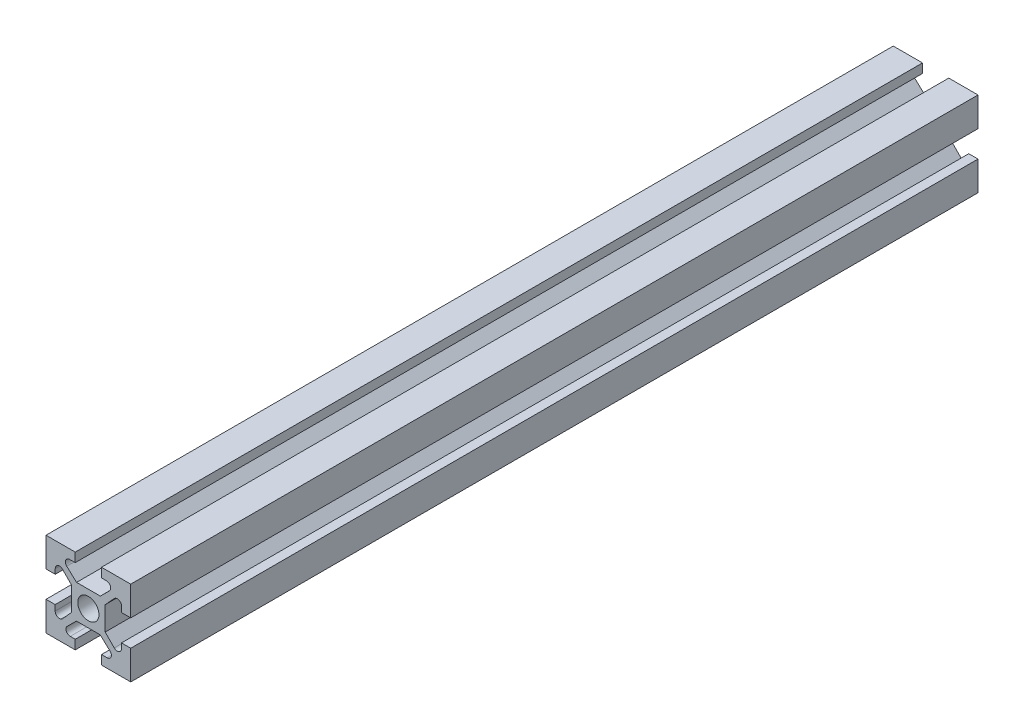
SolidWorks part; units mm, degrees
ref_plane "Front Plane" through (0, 0, 0) normal (0, 0, 1) x (1, 0, 0)
ref_plane "Top Plane" through (0, 0, 0) normal (0, 1, 0) x (1, 0, 0)
ref_plane "Right Plane" through (0, 0, 0) normal (1, 0, 0) x (0, 0, -1)
sketch "Sketch2" plane through (0, 0, 0) normal (0, 0, 1) x (1, 0, 0)
  line L0 (-295.6365, 99.3001) -> (355.6968, 99.3001) construction
  line L1 (53, 177) -> (305, 177) construction
  line L2 (0, 9.9554) -> (0, -10.0446) construction
  line L7 (-10, -10) -> (-3.1, -10)
  line L8 (-10, -10) -> (-10, -3.1)
  line L9 (-10, 10) -> (-3.1, 10)
  line L10 (10, -10) -> (10, -3.1)
  line L11 (-10, -10) -> (10, 10) construction
  line L12 (-10, 10) -> (10, -10) construction
  line L13 (-10, 0) -> (10, 0) construction
  line L14 (-10, 3.1) -> (-7.8186, 3.1)
  line L15 (-7.8186, 3.1) -> (-7.8186, 4.2854)
  line L16 (-6.1072, 4.9882) -> (-3.9647, 2.8197)
  line L17 (-3.9647, 2.8197) -> (-3.9647, 0)
  line L18 (-3.1, 10) -> (-3.1, 7.839)
  line L19 (-3.1, 7.839) -> (-4.4279, 7.839)
  line L20 (-5.1052, 6.1033) -> (-2.7827, 3.9647)
  line L21 (-2.7827, 3.9647) -> (0, 3.9647)
  line L22 (3.1, 10) -> (3.1, 7.8186)
  line L23 (3.1, 7.8186) -> (4.2854, 7.8186)
  line L24 (4.9882, 6.1072) -> (2.8197, 3.9647)
  line L25 (2.8197, 3.9647) -> (0, 3.9647)
  line L26 (6.1033, 5.1052) -> (3.9647, 2.7827)
  line L27 (3.9647, 2.7827) -> (3.9647, 0)
  line L28 (7.839, 3.1) -> (7.839, 4.4279)
  line L29 (10, 3.1) -> (7.839, 3.1)
  line L30 (10, -3.1) -> (7.8186, -3.1)
  line L31 (7.8186, -3.1) -> (7.8186, -4.2854)
  line L32 (6.1072, -4.9882) -> (3.9647, -2.8197)
  line L33 (3.9647, -2.8197) -> (3.9647, 0)
  line L34 (5.1052, -6.1033) -> (2.7827, -3.9647)
  line L35 (2.7827, -3.9647) -> (0, -3.9647)
  line L36 (3.1, -7.839) -> (4.4279, -7.839)
  line L37 (3.1, -10) -> (3.1, -7.839)
  line L38 (-3.1, -10) -> (-3.1, -7.8186)
  line L39 (-3.1, -7.8186) -> (-4.2854, -7.8186)
  line L40 (-4.9882, -6.1072) -> (-2.8197, -3.9647)
  line L41 (-2.8197, -3.9647) -> (0, -3.9647)
  line L42 (-6.1033, -5.1052) -> (-3.9647, -2.7827)
  line L43 (-3.9647, -2.7827) -> (-3.9647, 0)
  line L44 (-7.839, -3.1) -> (-7.839, -4.4279)
  line L45 (-10, -3.1) -> (-7.839, -3.1)
  line L46 (3.1, 10) -> (10, 10)
  line L47 (10, 3.1) -> (10, 10)
  line L48 (3.1, -10) -> (10, -10)
  line L49 (-10, 3.1) -> (-10, 10)
  circle A1 centre (0, 0) radius 2.5
  arc A2 (-4.4279, 7.839) -> (-5.1052, 6.1033) centre (-4.4279, 6.839) ccw
  arc A3 (-7.8186, 4.2854) -> (-6.1072, 4.9882) centre (-6.8186, 4.2854) cw
  arc A4 (4.2854, 7.8186) -> (4.9882, 6.1072) centre (4.2854, 6.8186) cw
  arc A5 (7.839, 4.4279) -> (6.1033, 5.1052) centre (6.839, 4.4279) ccw
  arc A6 (7.8186, -4.2854) -> (6.1072, -4.9882) centre (6.8186, -4.2854) cw
  arc A7 (4.4279, -7.839) -> (5.1052, -6.1033) centre (4.4279, -6.839) ccw
  arc A8 (-4.2854, -7.8186) -> (-4.9882, -6.1072) centre (-4.2854, -6.8186) cw
  arc A9 (-7.839, -4.4279) -> (-6.1033, -5.1052) centre (-6.839, -4.4279) ccw
extrude "Boss-Extrude1" add sketch "Sketch2" along normal blind 200
